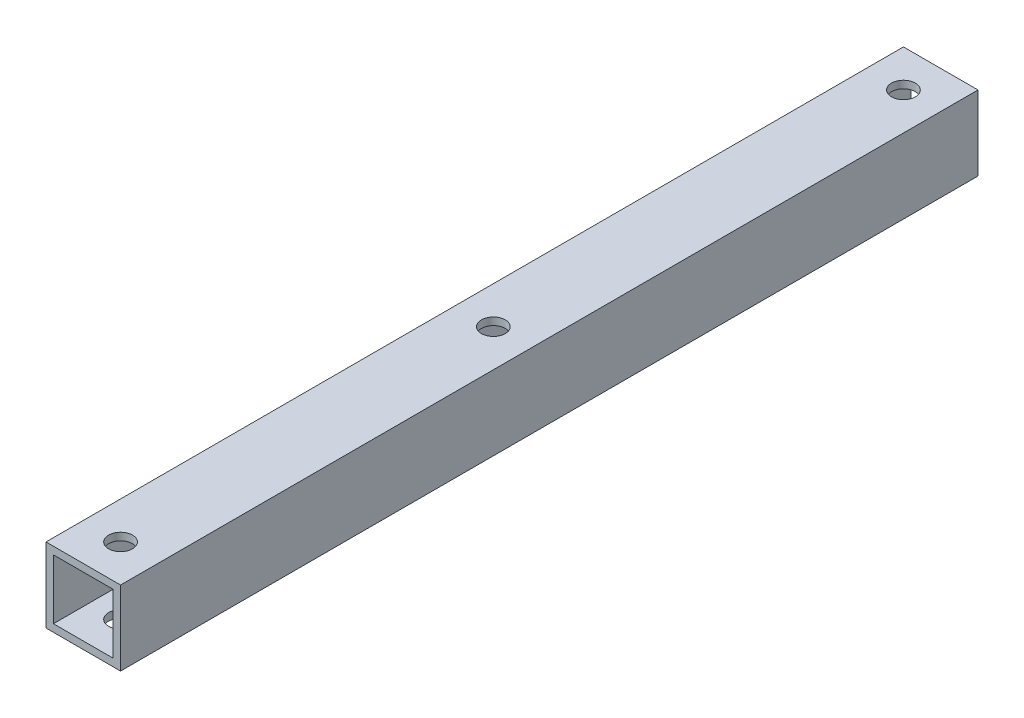
SolidWorks part; units mm, degrees
material "6061 合金"
ref_plane "正面" through (0, 0, 0) normal (0, 0, 1) x (1, 0, 0)
ref_plane "平面" through (0, 0, 0) normal (0, 1, 0) x (1, 0, 0)
ref_plane "右側面" through (0, 0, 0) normal (1, 0, 0) x (0, 0, -1)
sketch "断面 スケッチ" plane through (0, 0, 0) normal (0, 0, 1) x (1, 0, 0)
  line L1 (-5, -5) -> (5, -5)
  line L2 (-5, -5) -> (-5, 5)
  line L3 (-5, 5) -> (5, 5)
  line L4 (5, -5) -> (5, 5)
  line L5 (-5, -5) -> (5, 5) construction
  line L6 (-5, 5) -> (5, -5) construction
  point P0 (0, 0)
  dimension "D1" = 10
extrude "フレーム全長" add sketch "断面 スケッチ" along normal blind 115 thin thin type one direction reverse wall 1
sketch "上面穴 スケッチ" plane through (0, 5, 0) normal (0, 1, 0) x (1, 0, 0)
  line L0 (0, 0) -> (0, -115) construction
  line L1 (5, 0) -> (-5, 0) construction
  line L2 (5, -115) -> (-5, -115) construction
  line L3 (-5, -57.5) -> (5, -57.5) construction
  line L4 (-5, -115) -> (-5, 0) construction
  line L5 (5, -115) -> (5, 0) construction
  circle A0 centre (0, -5) radius 1.6
  circle A1 centre (0, -60) radius 1.6
  circle A2 centre (0, -110) radius 1.6
  dimension "D1" = 5
  dimension "D2" = 3.2
  dimension "D3" = 55
  dimension "D4" = 50
sketch "側面穴 スケッチ" plane through (5, 0, 0) normal (1, 0, 0) x (0, 0, -1)
  line L0 (0, 0) -> (-115, 0) construction
  line L1 (0, -5) -> (0, 5) construction
  line L2 (-115, -5) -> (-115, 5) construction
  line L3 (-57.5, 5) -> (-57.5, -5) construction
  line L4 (-115, 5) -> (0, 5) construction
  line L5 (-115, -5) -> (0, -5) construction
  circle A0 centre (-15, 0) radius 1.6
  dimension "D1" = 15
  dimension "D2" = 3.2
extrude "上面穴貫通" cut sketch "上面穴 スケッチ" against normal through all
extrude "側面穴貫通" [suppressed] cut sketch "側面穴 スケッチ" against normal through all
fillet "フィレット" [suppressed] radius 5
